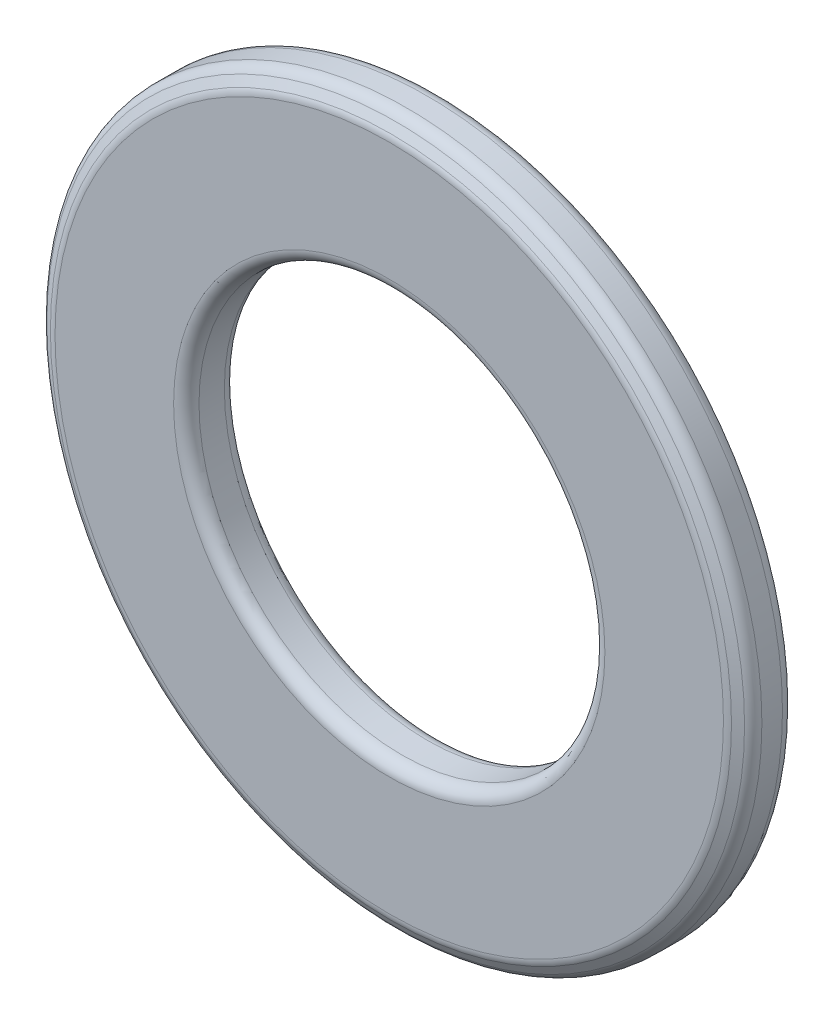
SolidWorks part; units mm, degrees
ref_plane "Front Plane" through (0, 0, 0) normal (0, 0, 1) x (1, 0, 0)
ref_plane "Top Plane" through (0, 0, 0) normal (0, 1, 0) x (1, 0, 0)
ref_plane "Right Plane" through (0, 0, 0) normal (1, 0, 0) x (0, 0, -1)
sketch "Sketch1" plane through (0, 0, 0) normal (0, 0, 1) x (1, 0, 0)
  circle A0 centre (15.23, -44.7825) radius 4
  circle A1 centre (15.23, -44.7825) radius 7
  dimension "D1" = 14
extrude "Boss-Extrude1" add sketch "Sketch1" along normal blind 1
chamfer "Chamfer1" distance 0.2 angle 60 1 edges at (22.23, -44.7825, 1)
fillet "Fillet1" radius 0.25 5 edges at (19.23, -44.7825, 0) (22.23, -44.7825, 0) (22.23, -44.7825, 0.8) (19.23, -44.7825, 1) (21.8836, -44.7825, 1)
